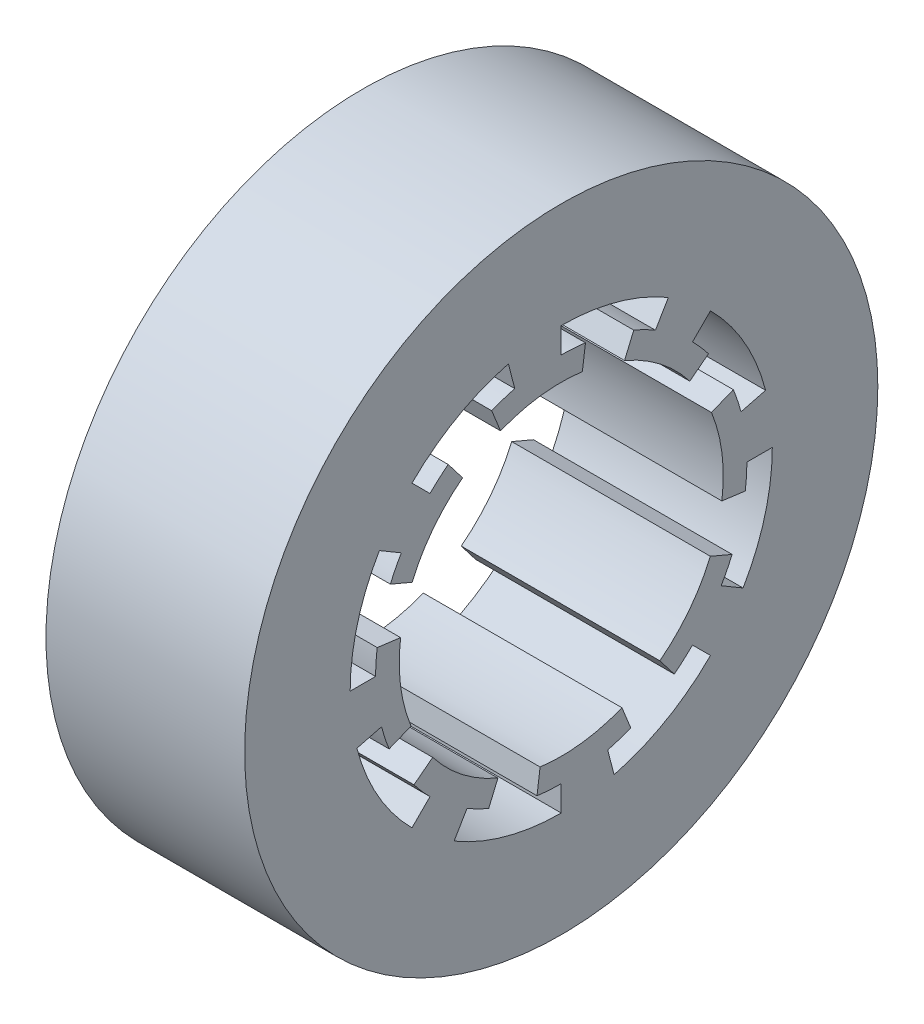
SolidWorks part; units mm, degrees
material "TPU 95A"
ref_plane "Front Plane" through (0, 0, 0) normal (1, 0, 0) x (0, 1, 0)
ref_plane "Top Plane" through (0, 0, 0) normal (0, 0, 1) x (0, 1, 0)
ref_plane "Right Plane" through (0, 0, 0) normal (0, 1, 0) x (-1, 0, 0)
sketch "Sketch1" plane through (0, 0, 0) normal (1, 0, 0) x (0, 1, 0)
  circle A0 centre (0, 0) radius 32.385
  circle A1 centre (0, 0) radius 21.59
  dimension "D1" = 64.77
  dimension "D2" = 43.18
extrude "Boss-Extrude1" add sketch "Sketch1" along normal blind 20.32
sketch "Sketch3" plane through (0, 0, 0) normal (1, 0, 0) x (0, 1, 0)
  line L0 (0, 0) -> (0, 21.59) construction
  line L1 (0, 0) -> (-5.4057, 20.9023) construction
  line L2 (0, 0) -> (-10.6314, 18.791) construction
  line L3 (0, 0) -> (5.5879, 20.8543) construction
  line L4 (-5.4057, 20.9023) -> (-4.7538, 18.3817)
  line L5 (0, 0) -> (-7.1125, 17.604) construction
  line L6 (0, 0) -> (2.4782, 18.8241) construction
  line L7 (0, 21.59) -> (0, 18.9865)
  line L8 (-7.1125, 17.604) -> (-6.2085, 15.3667)
  line L9 (2.4782, 18.8241) -> (2.1633, 16.4317)
  circle A0 centre (0, 0) radius 21.59 construction
  circle A1 centre (0, 0) radius 18.9865 construction
  circle A3 centre (0, 0) radius 16.5735 construction
  arc A4 (-4.7538, 18.3817) -> (-7.1125, 17.604) centre (0, 0) ccw
  arc A5 (0, 18.9865) -> (2.4782, 18.8241) centre (0, 0) cw
  arc A6 (-6.2085, 15.3667) -> (2.1633, 16.4317) centre (0, 0) cw
  arc A7 (-5.4057, 20.9023) -> (0, 21.59) centre (0, 0) cw
  dimension "D6" = 43.18
  dimension "D7" = 37.973
  dimension "D8" = 33.147
  dimension "D1" = 14.5
  dimension "D2" = 15
  dimension "D3" = 15
  dimension "D4" = 7.5
  dimension "D5" = 7.5
extrude "Boss-Extrude2" add sketch "Sketch3" along normal up to surface (20.32 mm away) up to face at (20.32, 0, -32.385)
sketch "Sketch4" plane through (0, 0, 0) normal (0, 0, 1) x (0, 1, 0)
  line L0 (0, 0) -> (0, -7.3257) construction
  line L1 (32.385, 0) -> (-32.385, 0) construction
pattern_circular "CirPattern1" count 8 every 45 about axis through (0, 0, 0) along (1, 0, 0) of "Boss-Extrude2"
